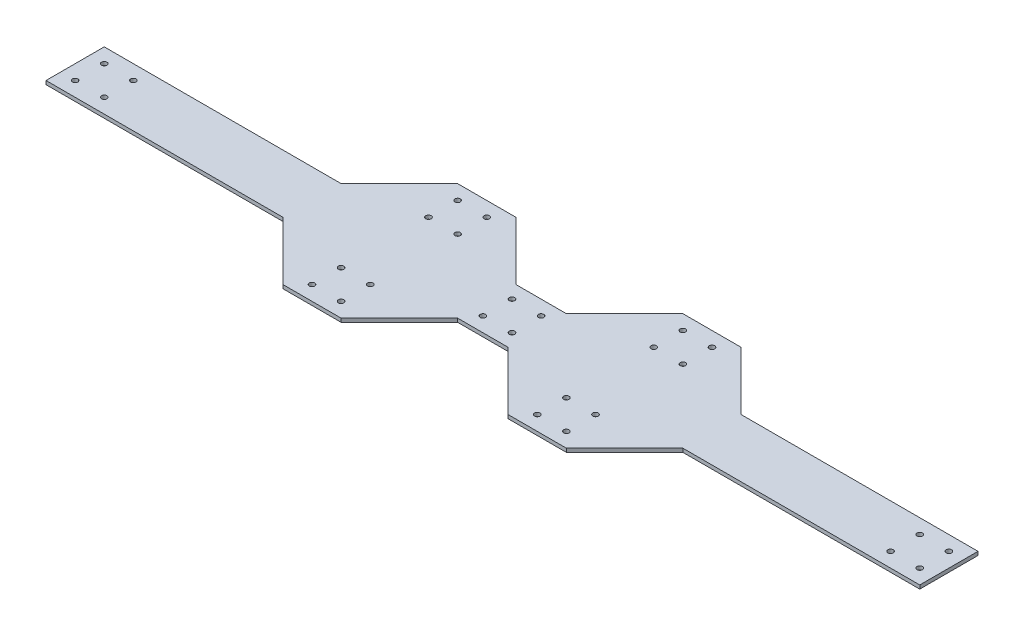
SolidWorks part; units mm, degrees
ref_plane "Front Plane" through (0, 0, 0) normal (0, 0, 1) x (1, 0, 0)
ref_plane "Top Plane" through (0, 0, 0) normal (0, 1, 0) x (1, 0, 0)
ref_plane "Right Plane" through (0, 0, 0) normal (1, 0, 0) x (0, 0, -1)
sketch "Sketch2" plane through (0, 0, 0) normal (0, 1, 0) x (1, 0, 0)
  line L0 (0, 0) -> (0, 50000) construction
  line L1 (22.0266, 25.4) -> (72.8266, 76.2)
  line L2 (72.8266, 76.2) -> (123.6266, 76.2)
  line L3 (123.6266, 76.2) -> (174.4266, 25.4)
  line L4 (174.4266, 25.4) -> (381, 25.4)
  line L5 (381, 25.4) -> (381, -25.4)
  line L6 (381, -25.4) -> (174.4266, -25.4)
  line L7 (174.4266, -25.4) -> (123.6266, -76.2)
  line L8 (123.6266, -76.2) -> (72.8266, -76.2)
  line L9 (72.8266, -76.2) -> (22.0266, -25.4)
  line L10 (22.0266, -25.4) -> (-22.0266, -25.4)
  line L11 (22.0266, 25.4) -> (-22.0266, 25.4)
  line L12 (-72.8266, -76.2) -> (-22.0266, -25.4)
  line L13 (-123.6266, -76.2) -> (-72.8266, -76.2)
  line L14 (-174.4266, -25.4) -> (-123.6266, -76.2)
  line L15 (-381, -25.4) -> (-174.4266, -25.4)
  line L16 (-381, 25.4) -> (-381, -25.4)
  line L17 (-174.4266, 25.4) -> (-381, 25.4)
  line L18 (-123.6266, 76.2) -> (-174.4266, 25.4)
  line L19 (-72.8266, 76.2) -> (-123.6266, 76.2)
  line L20 (-22.0266, 25.4) -> (-72.8266, 76.2)
  point P14 (0, 0)
  point P16 (0, 25.4)
  point P17 (0, -25.4)
  point P18 (381, 0)
  dimension "D1" = 152.4
  dimension "D2" = 762
  dimension "D3" = 50.8
  dimension "D4" = 72.8266
extrude "Boss-Extrude1" add sketch "Sketch2" along normal blind 3.175
sketch "Sketch3" plane through (0, 3.175, 0) normal (0, 1, 0) x (1, 0, 0)
  line L0 (-110.9266, 38.1) -> (-85.5266, 63.5) construction
  line L1 (-149.0266, 50.8) -> (-47.4266, 50.8) construction
  line L2 (-123.6266, 76.2) -> (-174.4266, 25.4) construction
  line L3 (-22.0266, 25.4) -> (-72.8266, 76.2) construction
  line L4 (0, 0) -> (-14.3721, 0) construction
  line L5 (0, 0) -> (0, 50000) construction
  line L6 (149.0266, 50.8) -> (47.4266, 50.8) construction
  line L7 (110.9266, 38.1) -> (85.5266, 63.5) construction
  line L10 (-381, 25.4) -> (-381, -25.4) construction
  circle A0 centre (-110.9266, 63.5) radius 2.3813
  circle A1 centre (-85.5266, 63.5) radius 2.3813
  circle A2 centre (-110.9266, 38.1) radius 2.3813
  circle A3 centre (-85.5266, 38.1) radius 2.3813
  circle A4 centre (-85.5266, -38.1) radius 2.3813
  circle A5 centre (-110.9266, -38.1) radius 2.3813
  circle A6 centre (-85.5266, -63.5) radius 2.3813
  circle A7 centre (-110.9266, -63.5) radius 2.3813
  circle A8 centre (110.9266, -63.5) radius 2.3813
  circle A9 centre (85.5266, -63.5) radius 2.3813
  circle A10 centre (110.9266, -38.1) radius 2.3813
  circle A11 centre (85.5266, -38.1) radius 2.3813
  circle A12 centre (85.5266, 38.1) radius 2.3813
  circle A13 centre (110.9266, 38.1) radius 2.3813
  circle A14 centre (85.5266, 63.5) radius 2.3813
  circle A15 centre (110.9266, 63.5) radius 2.3813
  circle A22 centre (-342.9, -12.7) radius 2.3813
  circle A23 centre (-368.3, -12.7) radius 2.3813
  circle A24 centre (-368.3, 12.7) radius 2.3813
  circle A25 centre (-342.9, 12.7) radius 2.3813
  circle A26 centre (342.9, 12.7) radius 2.3813
  circle A27 centre (368.3, 12.7) radius 2.3813
  circle A28 centre (368.3, -12.7) radius 2.3813
  circle A29 centre (342.9, -12.7) radius 2.3813
  circle A30 centre (-12.7, 12.7) radius 2.3813
  circle A31 centre (12.7, 12.7) radius 2.3813
  circle A32 centre (12.7, -12.7) radius 2.3813
  circle A33 centre (-12.7, -12.7) radius 2.3812
  point P16 (-98.2266, 50.8)
  point P17 (-98.2266, 50.8)
  point P28 (-98.2266, -50.8)
  point P50 (98.2266, -50.8)
  point P51 (98.2266, 50.8)
  point P52 (25.7173, 7.4429)
  point P53 (0, 0)
  point P67 (0, 0)
  dimension "D1" = 4.7625
  dimension "D7" = 4.7625
  dimension "D2" = 25.4
  dimension "D3" = 25.4
  dimension "D4" = 25.4
  dimension "D5" = 25.4
  dimension "D6" = 12.7
  dimension "D8" = 12.7
  dimension "D9" = 12.7
  dimension "D10" = 4
extrude "Cut-Extrude1" cut sketch "Sketch3" against normal through all both and the other way through all
